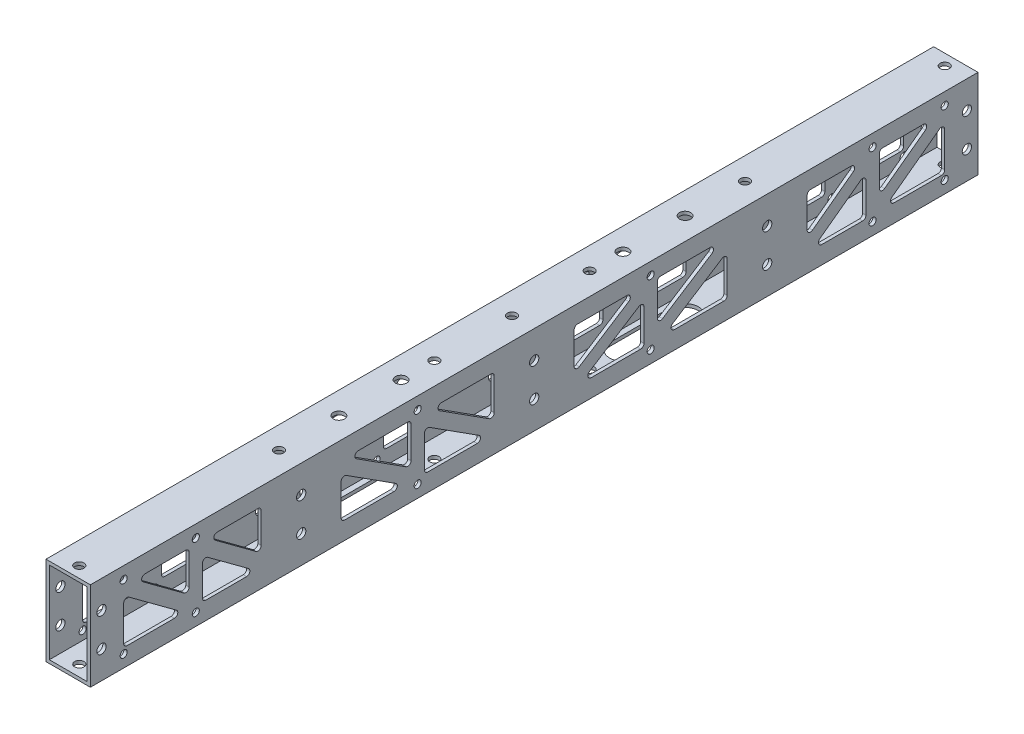
SolidWorks part; units mm, degrees
material "6061 合金"
ref_plane "前视基准面" through (0, 0, 0) normal (0, 0, 1) x (1, 0, 0)
ref_plane "上视基准面" through (0, 0, 0) normal (0, 1, 0) x (1, 0, 0)
ref_plane "右视基准面" through (0, 0, 0) normal (1, 0, 0) x (0, 0, -1)
sketch "草图1" plane through (0, 0, 0) normal (0, 0, 1) x (1, 0, 0)
  line L0 (-8.5, 18.5) -> (8.5, 18.5)
  line L1 (-10, 20) -> (10, 20)
  line L2 (-10, 20) -> (-10, -20)
  line L3 (-10, -20) -> (10, -20)
  line L4 (10, 20) -> (10, -20)
  line L5 (-10, 20) -> (10, -20) construction
  line L6 (-10, -20) -> (10, 20) construction
  line L7 (8.5, 18.5) -> (8.5, -18.5)
  line L8 (-8.5, -18.5) -> (8.5, -18.5)
  line L9 (-8.5, 18.5) -> (-8.5, -18.5)
  point P0 (0, 0)
  dimension "D1" = 20
  dimension "D2" = 40
  dimension "D3" = 1.5
extrude "凸台-拉伸1" add sketch "草图1" along normal mid plane 400
sketch "草图2" plane through (0, 0, 0) normal (1, 0, 0) x (0, 0, -1)
  line L0 (200, -20) -> (200, 20) construction
  line L1 (-185, 12) -> (185, 12)
  line L2 (-185, 12) -> (-185, -12)
  line L3 (-185, -12) -> (185, -12)
  line L4 (185, 12) -> (185, -12)
  line L5 (-185, 12) -> (185, -12) construction
  line L6 (-185, -12) -> (185, 12) construction
  line L7 (-200, -20) -> (200, -20) construction
  line L8 (0, 12) -> (0, -12)
  line L9 (-90, 12) -> (-90, -12)
  line L10 (90, 12) -> (90, -12)
  line L11 (-120, 12) -> (-120, -12)
  line L12 (120, 12) -> (120, -12)
  line L13 (-15, 12) -> (-15, -12)
  line L14 (15, 12) -> (15, -12)
  line L15 (-185, 12) -> (-152.5, -12)
  line L16 (-152.5, -12) -> (-152.5, 12)
  line L17 (-152.5, 12) -> (-120, -12)
  line L18 (-90, 12) -> (-52.5, -12)
  line L19 (-52.5, -12) -> (-52.5, 12)
  line L20 (-52.5, 12) -> (-15, -12)
  line L21 (15, -12) -> (52.5, 12)
  line L22 (52.5, 12) -> (52.5, -12)
  line L23 (52.5, -12) -> (90, 12)
  line L24 (120, -12) -> (152.5, 12)
  line L25 (152.5, 12) -> (152.5, -12)
  line L26 (152.5, -12) -> (185, 12)
  line L27 (-186.7821, 9.5867) -> (-149.5, -17.9447)
  line L28 (-149.5, -17.9447) -> (-149.5, 6.0553)
  line L29 (-149.5, 6.0553) -> (-117, -17.9447)
  line L30 (-117, 12) -> (-117, -17.9447)
  line L31 (-18, 12) -> (-18, -6.5182)
  line L32 (-55.5, 17.4818) -> (-18, -6.5182)
  line L33 (-55.5, -6.5182) -> (-55.5, 17.4818)
  line L34 (-93, 17.4818) -> (-55.5, -6.5182)
  line L35 (-93, 17.4818) -> (-93, -12)
  line L36 (12, 12) -> (12, -17.4818)
  line L37 (12, -17.4818) -> (49.5, 6.5182)
  line L38 (49.5, 6.5182) -> (49.5, -17.4818)
  line L39 (49.5, -17.4818) -> (87, 6.5182)
  line L40 (87, 6.5182) -> (87, -12)
  line L41 (117, 12) -> (117, -17.9447)
  line L42 (117, -17.9447) -> (149.5, 6.0553)
  line L43 (149.5, 6.0553) -> (149.5, -17.9447)
  line L44 (149.5, -17.9447) -> (186.7821, 9.5867)
  line L45 (-183.2179, 14.4133) -> (-155.5, -6.0553)
  line L46 (-155.5, -6.0553) -> (-155.5, 17.9447)
  line L47 (-155.5, 17.9447) -> (-123, -6.0553)
  line L48 (-123, 12) -> (-123, -6.0553)
  line L49 (-12, 12) -> (-12, -17.4818)
  line L50 (-49.5, 6.5182) -> (-12, -17.4818)
  line L51 (-49.5, -17.4818) -> (-49.5, 6.5182)
  line L52 (-87, 6.5182) -> (-49.5, -17.4818)
  line L53 (-87, 6.5182) -> (-87, -12)
  line L54 (18, 12) -> (18, -6.5182)
  line L55 (18, -6.5182) -> (55.5, 17.4818)
  line L56 (55.5, 17.4818) -> (55.5, -6.5182)
  line L57 (55.5, -6.5182) -> (93, 17.4818)
  line L58 (93, 17.4818) -> (93, -12)
  line L59 (123, 12) -> (123, -6.0553)
  line L60 (123, -6.0553) -> (155.5, 17.9447)
  line L61 (155.5, 17.9447) -> (155.5, -6.0553)
  line L62 (155.5, -6.0553) -> (183.2179, 14.4133)
  point P0 (0, 0)
  dimension "D1" = 15
  dimension "D2" = 8
  dimension "D3" = 90
  dimension "D4" = 90
  dimension "D5" = 30
  dimension "D6" = 30
  dimension "D7" = 15
  dimension "D8" = 15
  dimension "D9" = 3
  dimension "D10" = 3
extrude "切除-拉伸1" cut sketch "草图2" against normal mid plane 30 contours L27 L2 L3 | L45 L46 L1 | L29 L28 L3 | L48 L1 L47 | L52 L53 L3 | L1 L34 L33 | L51 L3 L50 | L1 L32 L31 | L38 L37 L3 | L54 L55 L1 | L56 L57 L1 | L40 L39 L3 | L59 L60 L1 | L43 L42 L3 | L61 L62 L1 | L44 L3 L4
fillet "圆角1" radius 1.5 48 edges at (9.25, -6.5182, 55.5) (9.25, 12, 84.4347) (9.25, 12, 55.5) (9.25, -12, 20.5653) (9.25, -12, 49.5) (9.25, 6.5182, 49.5) (9.25, -6.5182, 18) (9.25, 12, 46.9347) (9.25, 12, 18) (9.25, -12, -20.5653) (9.25, 6.5182, -49.5) (9.25, -12, -49.5) (9.25, -12, 149.5) (9.25, 6.0553, 149.5) (9.25, -12, 125.0501) (9.25, 12, 147.4499) (9.25, 12, 123) (9.25, -6.0553, 123) (9.25, -12, 87) (9.25, 6.5182, 87) (9.25, -12, 58.0653) (9.25, -12, -125.0501) (9.25, 6.0553, -149.5) (9.25, -12, -149.5) (9.25, -12, -185) (9.25, -12, -157.5501) (9.25, 8.2707, -185) (9.25, -12, -58.0653) (9.25, 6.5182, -87) (9.25, -12, -87) (9.25, 8.2707, 185) (9.25, -12, 157.5501) (9.25, 12, -123) (9.25, 12, -147.4499) (9.25, -6.0553, -123) (9.25, 12, -55.5) (9.25, 12, -84.4347) (9.25, -6.5182, -55.5) (9.25, 12, -18) (9.25, 12, -46.9347) (9.25, -6.5182, -18) (9.25, 12, -155.5) (9.25, 12, -179.9499) (9.25, -6.0553, -155.5) (9.25, 12, 179.9499) (9.25, 12, 155.5) (9.25, -6.0553, 155.5) (9.25, -12, 185)
fillet "圆角2" radius 1.5 48 edges at (-9.25, 12, 55.5) (-9.25, -6.5182, 55.5) (-9.25, 12, 84.4347) (-9.25, 12, 18) (-9.25, -6.5182, 18) (-9.25, 12, 46.9347) (-9.25, -12, 125.0501) (-9.25, -12, 149.5) (-9.25, 6.0553, 149.5) (-9.25, -12, 58.0653) (-9.25, -12, 87) (-9.25, 6.5182, 87) (-9.25, 8.2707, -185) (-9.25, -12, -185) (-9.25, -12, -157.5501) (-9.25, 12, -46.9347) (-9.25, -6.5182, -18) (-9.25, 12, -18) (-9.25, 12, -84.4347) (-9.25, -6.5182, -55.5) (-9.25, 12, -55.5) (-9.25, -12, 157.5501) (-9.25, 8.2707, 185) (-9.25, 12, -147.4499) (-9.25, -6.0553, -123) (-9.25, 12, -123) (-9.25, -12, -87) (-9.25, -12, -58.0653) (-9.25, 6.5182, -87) (-9.25, 12, -179.9499) (-9.25, -6.0553, -155.5) (-9.25, 12, -155.5) (-9.25, -12, -149.5) (-9.25, -12, -125.0501) (-9.25, 6.0553, -149.5) (-9.25, -6.0553, 123) (-9.25, 12, 147.4499) (-9.25, 12, 123) (-9.25, 12, 155.5) (-9.25, -6.0553, 155.5) (-9.25, 12, 179.9499) (-9.25, -12, -49.5) (-9.25, -12, -20.5653) (-9.25, 6.5182, -49.5) (-9.25, 6.5182, 49.5) (-9.25, -12, 20.5653) (-9.25, -12, 49.5) (-9.25, -12, 185)
sketch "草图3" plane through (-10, 0, 0) normal (-1, 0, 0) x (0, 0, 1)
  line L0 (200, 20) -> (200, -20) construction
  line L1 (-195, 7.5) -> (195, 7.5) construction
  line L2 (-195, 7.5) -> (-195, -7.5) construction
  line L3 (-195, -7.5) -> (195, -7.5) construction
  line L4 (195, 7.5) -> (195, -7.5) construction
  line L5 (-195, 7.5) -> (195, -7.5) construction
  line L6 (-195, -7.5) -> (195, 7.5) construction
  line L7 (200, 20) -> (-200, 20) construction
  line L8 (0, 7.5) -> (0, -7.5) construction
  line L9 (105, 7.5) -> (-105, 7.5) construction
  line L10 (105, 7.5) -> (105, -7.5) construction
  line L11 (105, -7.5) -> (-105, -7.5) construction
  line L12 (-105, 7.5) -> (-105, -7.5) construction
  line L13 (105, 7.5) -> (-105, -7.5) construction
  line L14 (105, -7.5) -> (-105, 7.5) construction
  circle A0 centre (-195, -7.5) radius 2.1
  circle A1 centre (-195, 7.5) radius 2.1
  circle A2 centre (-105, 7.5) radius 2.1
  circle A3 centre (-105, -7.5) radius 2.1
  circle A4 centre (0, -7.5) radius 2.1
  circle A5 centre (0, 7.5) radius 2.1
  circle A6 centre (105, 7.5) radius 2.1
  circle A7 centre (105, -7.5) radius 2.1
  circle A8 centre (195, -7.5) radius 2.1
  circle A9 centre (195, 7.5) radius 2.1
  point P8 (0, 0)
  dimension "D8" = 4.2
  dimension "D1" = 390
  dimension "D2" = 15
  dimension "D3" = 5
  dimension "D4" = 12.5
  dimension "D5" = 15
  dimension "D6" = 210
  dimension "D7" = 90
extrude "切除-拉伸2" cut sketch "草图3" against normal through all
sketch "草图4" plane through (10, 0, 0) normal (1, 0, 0) x (0, 0, -1)
  line L0 (-200, -20) -> (200, -20) construction
  line L1 (-52.5, 14.5) -> (52.5, 14.5) construction
  line L2 (-52.5, 14.5) -> (-52.5, -14.5) construction
  line L3 (-52.5, -14.5) -> (52.5, -14.5) construction
  line L4 (52.5, 14.5) -> (52.5, -14.5) construction
  line L5 (-52.5, 14.5) -> (52.5, -14.5) construction
  line L6 (-52.5, -14.5) -> (52.5, 14.5) construction
  line L7 (-152.5, 14.5) -> (152.5, 14.5) construction
  line L8 (-152.5, 14.5) -> (-152.5, -14.5) construction
  line L9 (-152.5, -14.5) -> (152.5, -14.5) construction
  line L10 (152.5, 14.5) -> (152.5, -14.5) construction
  line L11 (-152.5, 14.5) -> (152.5, -14.5) construction
  line L12 (-152.5, -14.5) -> (152.5, 14.5) construction
  line L13 (-200, 20) -> (200, 20) construction
  line L14 (-155.5, 10.5) -> (-155.5, -3.0829) construction
  line L15 (155.5, -3.0829) -> (155.5, 10.5) construction
  line L16 (55.5, -3.7773) -> (55.5, 10.5) construction
  line L18 (185, 14.5) -> (-185, 14.5) construction
  line L19 (185, 14.5) -> (185, -14.5) construction
  line L20 (185, -14.5) -> (-185, -14.5) construction
  line L21 (-185, 14.5) -> (-185, -14.5) construction
  line L22 (185, 14.5) -> (-185, -14.5) construction
  line L23 (185, -14.5) -> (-185, 14.5) construction
  circle A0 centre (-152.5, -14.5) radius 1.6
  circle A1 centre (-52.5, -14.5) radius 1.6
  circle A2 centre (52.5, -14.5) radius 1.6
  circle A3 centre (152.5, -14.5) radius 1.6
  circle A4 centre (152.5, 14.5) radius 1.6
  circle A5 centre (52.5, 14.5) radius 1.6
  circle A6 centre (-52.5, 14.5) radius 1.6
  circle A7 centre (-152.5, 14.5) radius 1.6
  circle A8 centre (185, -14.5) radius 1.6
  circle A9 centre (185, 14.5) radius 1.6
  circle A10 centre (-185, -14.5) radius 1.6
  circle A11 centre (-185, 14.5) radius 1.6
  point P0 (0, 0)
  point P27 (0, 0)
  dimension "D6" = 3.2
  dimension "D1" = 5.5
  dimension "D2" = 5.5
  dimension "D3" = 3
  dimension "D4" = 3
  dimension "D5" = 3
  dimension "D7" = 185
extrude "切除-拉伸3" cut sketch "草图4" against normal through all
sketch "草图5" plane through (0, 20, 0) normal (0, 1, 0) x (1, 0, 0)
  line L0 (0, 195) -> (0, -195) construction
  line L2 (10, 200) -> (-10, 200) construction
  line L3 (0, 105) -> (0, -105) construction
  line L4 (0, 35) -> (0, -35) construction
  circle A1 centre (0, -105) radius 2.1
  circle A2 centre (0, 0) radius 2.1
  circle A3 centre (0, 105) radius 2.1
  circle A4 centre (0, 195) radius 2.1
  circle A5 centre (0, -195) radius 2.1
  circle A6 centre (0, -35) radius 2.1
  circle A7 centre (0, 35) radius 2.1
  point P3 (0, 0)
  point P4 (0, 0)
  point P10 (0, 0)
  dimension "D4" = 4.2
  dimension "D1" = 390
  dimension "D2" = 5
  dimension "D3" = 210
  dimension "D5" = 70
extrude "切除-拉伸4" cut sketch "草图5" against normal through all
sketch "草图6" plane through (0, 20, 0) normal (0, 1, 0) x (1, 0, 0)
  circle A0 centre (0, -78) radius 2.55 construction
  circle A1 centre (0, -50) radius 2.55 construction
  circle A2 centre (0, 50) radius 2.55 construction
  circle A3 centre (0, 78) radius 2.55 construction
  circle A4 centre (0, -78) radius 2.55
  circle A5 centre (0, -50) radius 2.55
  circle A6 centre (0, 50) radius 2.55
  circle A7 centre (0, 78) radius 2.55
extrude "切除-拉伸5" cut sketch "草图6" against normal through all
sketch "草图7" plane through (0, -20, 0) normal (0, -1, 0) x (1, 0, 0)
  line L0 (0, 78) -> (0, 50) construction
  line L1 (6, 78) -> (6, 50)
  line L2 (-6, 78) -> (-6, 50)
  line L3 (0, -50) -> (0, -78) construction
  line L4 (6, -50) -> (6, -78)
  line L5 (-6, -50) -> (-6, -78)
  arc A0 (6, 78) -> (-6, 78) centre (0, 78) ccw
  arc A1 (-6, 50) -> (6, 50) centre (0, 50) ccw
  arc A2 (6, -50) -> (-6, -50) centre (0, -50) ccw
  arc A3 (-6, -78) -> (6, -78) centre (0, -78) ccw
  point P4 (0, 64)
  point P11 (0, -64)
  dimension "D1" = 6
extrude "切除-拉伸6" cut sketch "草图7" against normal up to next
